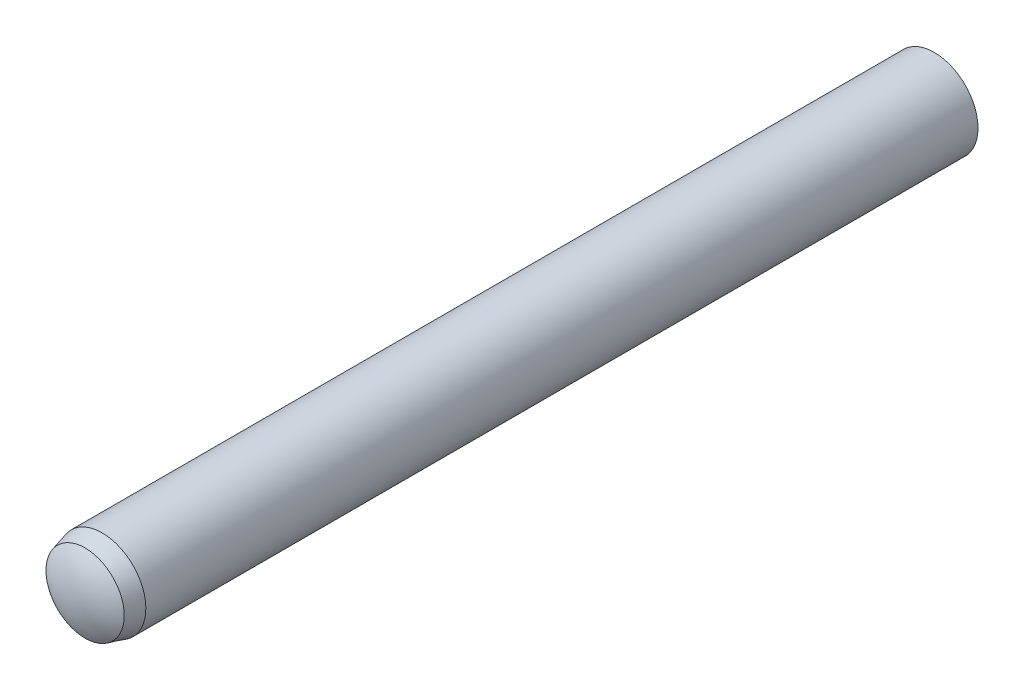
SolidWorks part; units mm, degrees
ref_plane "Front Plane" through (0, 0, 0) normal (0, 0, 1) x (1, 0, 0)
ref_plane "Top Plane" through (0, 0, 0) normal (0, 1, 0) x (1, 0, 0)
ref_plane "Right Plane" through (0, 0, 0) normal (1, 0, 0) x (0, 0, -1)
sketch "Sketch1" plane through (0, 0, 0) normal (0, 0, 1) x (1, 0, 0)
  circle A0 centre (0, 0) radius 1.5
  point P3 (0, 1.5)
  dimension "Diameter" = 3
sketch "Sketch2" plane through (0, 0, 0) normal (1, 0, 0) x (0, 0, -1)
  line L0 (-15, 0) -> (15, 0) construction
  line L1 (-15, 0) -> (-15, 1.5) construction
  line L2 (-15, 1.5) -> (15, 1.5)
  line L3 (15, 1.5) -> (15, 0) construction
  line L4 (-14.61, 1.3432) -> (-14.025, 1.5)
  arc A0 (-15, 0) -> (-14.61, 1.3432) centre (-12.4918, 0) cw
  arc A1 (15, 0) -> (14.55, 1.5) centre (12.275, 0) ccw
  point P2 (0, 0)
  point P11 (-12, 0)
  point P13 (12, 0)
  dimension "Length" = 30
  dimension "D1" = 15
  dimension "D2" = 0.45
  dimension "D3" = 0.975
  dimension "D4" = 0.585
  dimension "D5" = 3
  dimension "D6" = 3
sketch "Sketch3" plane through (0, 0, 0) normal (1, 0, 0) x (0, 0, -1)
  line L0 (-15, 0) -> (15, 0) construction
  line L1 (-14.61, 1.3432) -> (-14.025, 1.5) construction
  line L2 (-15, 0) -> (15, 0)
  line L3 (-14.61, 1.3432) -> (-14.025, 1.5)
  line L4 (-14.025, 1.5) -> (14.55, 1.5)
  arc A0 (15, 0) -> (14.55, 1.5) centre (12.275, 0) ccw construction
  arc A1 (-14.61, 1.3432) -> (-15, 0) centre (-12.4918, 0) ccw construction
  arc A2 (15, 0) -> (14.55, 1.5) centre (12.275, 0) ccw
  arc A3 (-14.61, 1.3432) -> (-15, 0) centre (-12.4918, 0) ccw
revolve "Revolve1" add sketch "Sketch3" angle 360 about L2
equation "\"D2@Sketch2\" = \"Diameter@Sketch1\" * .15"
equation "\"D3@Sketch2\" = \"Diameter@Sketch1\" * .325"
equation "\"D4@Sketch2\" = \"D3@Sketch2\" * .6"
equation "\"D5@Sketch2\"=\"Diameter@Sketch1\""
equation "\"D6@Sketch2\"=\"D5@sketch2\""
